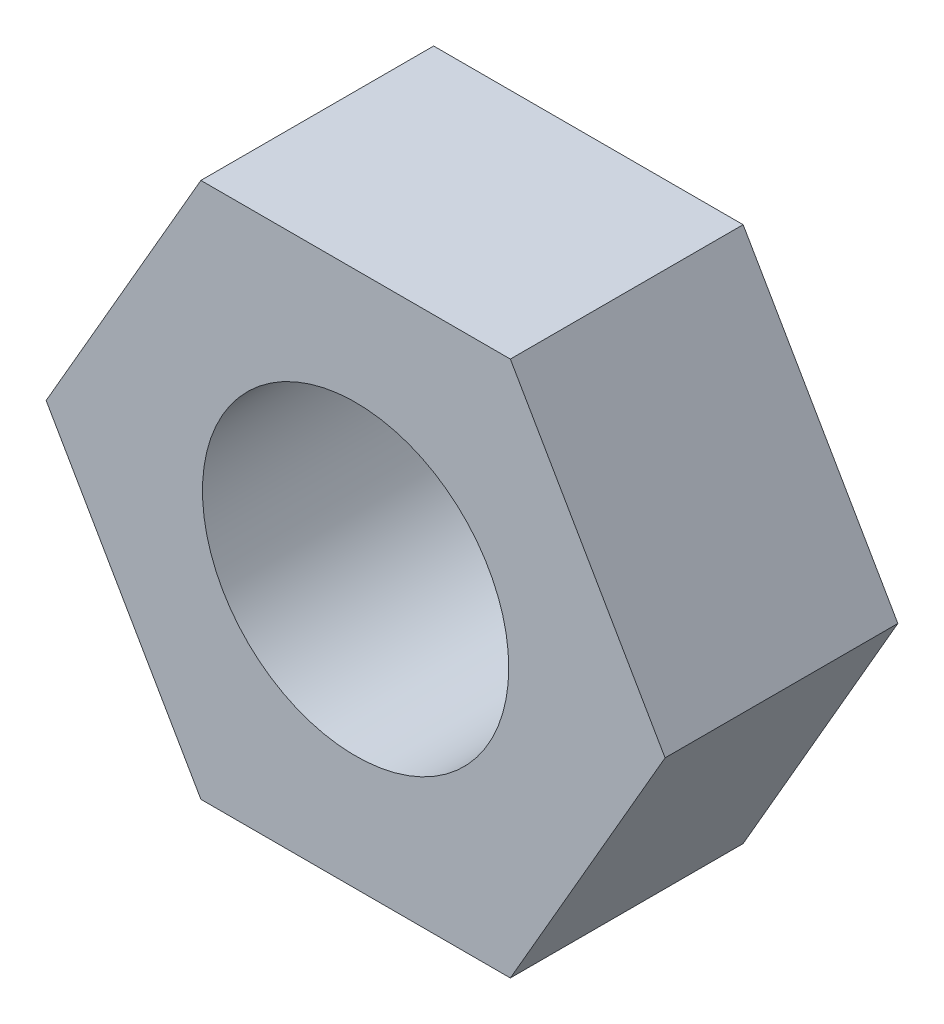
SolidWorks part; units mm, degrees
ref_plane "Front Plane" through (0, 0, 0) normal (0, 0, 1) x (1, 0, 0)
ref_plane "Top Plane" through (0, 0, 0) normal (0, 1, 0) x (1, 0, 0)
ref_plane "Right Plane" through (0, 0, 0) normal (1, 0, 0) x (0, 0, -1)
sketch "Sketch1" plane through (0, 0, 0) normal (0, 0, 1) x (1, 0, 0)
  line L1 (-6.4158, 0) -> (-3.2079, -5.5562)
  line L2 (-3.2079, -5.5562) -> (3.2079, -5.5563)
  line L3 (3.2079, -5.5563) -> (6.4158, 0)
  line L4 (6.4158, 0) -> (3.2079, 5.5562)
  line L5 (3.2079, 5.5562) -> (-3.2079, 5.5563)
  line L6 (-3.2079, 5.5563) -> (-6.4158, 0)
  circle A0 centre (0, 0) radius 5.5562 construction
  dimension "D1" = 11.1125
extrude "Boss-Extrude1" add sketch "Sketch1" along normal blind 4.826
sketch "Sketch2" plane through (0, 0, 4.826) normal (0, 0, 1) x (1, 0, 0)
  circle A0 centre (0, 0) radius 3.175
  dimension "D1" = 6.35
extrude "Cut-Extrude1" cut sketch "Sketch2" against normal through all
